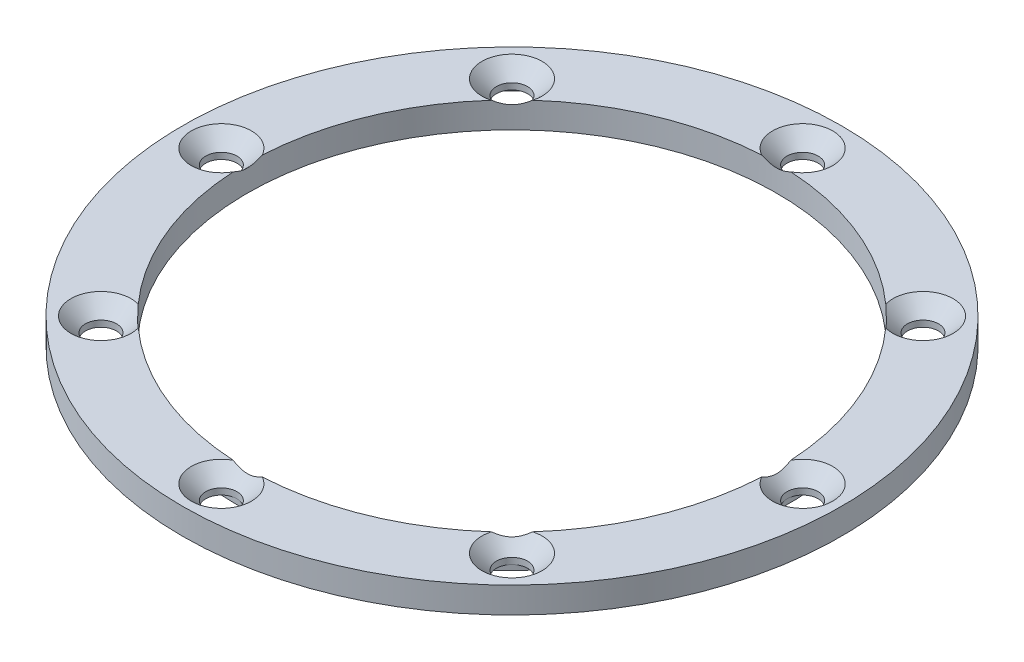
SolidWorks part; units mm, degrees
material "6061-T6 (SS)"
ref_plane "前视基准面" through (0, 0, 0) normal (0, 0, 1) x (1, 0, 0)
ref_plane "上视基准面" through (0, 0, 0) normal (0, 1, 0) x (1, 0, 0)
ref_plane "右视基准面" through (0, 0, 0) normal (1, 0, 0) x (0, 0, -1)
sketch "草图1" plane through (0, 0, 0) normal (0, 1, 0) x (1, 0, 0)
  circle A0 centre (0, 0) radius 30 construction
  circle A1 centre (0, 0) radius 25.5
  circle A2 centre (0, 0) radius 31.75
  dimension "D1" = 60
  dimension "D2" = 4.5
  dimension "D3" = 63.5
extrude "凸台-拉伸1" add sketch "草图1" along normal blind 2.5
sketch "草图2" plane through (0, 0, 0) normal (0, -1, 0) x (1, 0, 0)
  circle A0 centre (0, 0) radius 28 construction
  circle A2 centre (0, -28) radius 1.5
  circle A3 centre (-19.799, -19.799) radius 1.5
  circle A4 centre (-28, 0) radius 1.5
  circle A5 centre (-19.799, 19.799) radius 1.5
  circle A6 centre (0, 28) radius 1.5
  circle A7 centre (19.799, 19.799) radius 1.5
  circle A8 centre (28, 0) radius 1.5
  circle A9 centre (19.799, -19.799) radius 1.5
  point P24 (0, 0)
  dimension "D1" = 56
  dimension "D2" = 3
  dimension "D3" = 8
extrude "切除-拉伸1" cut sketch "草图2" against normal blind 10
sketch "草图3" plane through (0, 0, 0) normal (0, -1, 0) x (1, 0, 0)
  circle A0 centre (0, 0) radius 26.5
  circle A1 centre (0, 0) radius 30.1
  circle A4 centre (0, 0) radius 25.5 construction
  dimension "D1" = 60.2
  dimension "D2" = 1
extrude "切除-拉伸2" cut sketch "草图3" against normal blind 0.5
hole_wizard "打孔尺寸(%根据十字)槽沉头木螺钉的类型1" positions "3D草图1" profile "草图4" countersink size "M3" standard "GB" end condition through all
sketch3d "3D草图1"
  line L0 (0, 2.5, -28) -> (0, 0.5, -28) construction
  line L1 (19.799, 2.5, -19.799) -> (19.799, 0.5, -19.799) construction
  line L2 (28, 2.5, 0) -> (28, 0.5, 0) construction
  line L3 (19.799, 2.5, 19.799) -> (19.799, 0.5, 19.799) construction
  line L4 (0, 2.5, 28) -> (0, 0.5, 28) construction
  line L6 (-28, 2.5, 0) -> (-28, 0.5, 0) construction
  line L8 (-19.799, 2.5, -19.799) -> (-19.799, 0.5, -19.799) construction
  line L9 (-19.799, 2.5, 19.799) -> (-19.799, 0.5, 19.799) construction
  point P0 (0, 2.5, -28)
  point P4 (19.799, 2.5, -19.799)
  point P8 (28, 2.5, 0)
  point P12 (19.799, 2.5, 19.799)
  point P16 (0, 2.5, 28)
  point P24 (-28, 2.5, 0)
  point P35 (-19.799, 2.5, -19.799)
  point P39 (-19.799, 2.5, 19.799)
sketch "草图4" plane through (0, 2.5, -28) normal (1, 0, 0) x (0, 0, 1)
  line L0 (0, 0) -> (0, 2.5)
  line L1 (0, 2.5) -> (1.5, 2.5)
  line L2 (1.5, 2.5) -> (1.5, 1.4)
  line L3 (1.5, 1.4) -> (2.9, 0)
  line L5 (2.9, 0) -> (0, 0)
  line L6 (-1.5, 1.4) -> (-2.9, 0) construction
  line L11 (0, -6.35) -> (0, 107.95) construction
  dimension "通孔孔直径" = 3
  dimension "通孔孔深度" = 2.5
  dimension "近端锥形沉头孔直径" = 5.8
  dimension "近端锥形沉头孔角度" = 90
